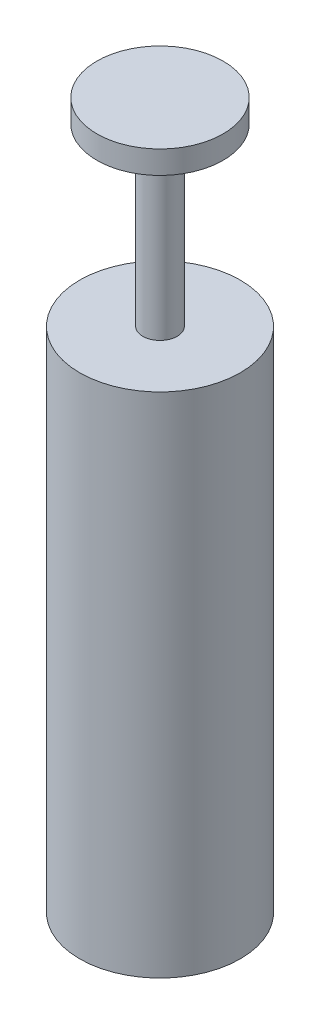
SolidWorks part; units mm, degrees
ref_plane "Front" through (0, 0, 0) normal (0, 0, 1) x (1, 0, 0)
ref_plane "Top" through (0, 0, 0) normal (0, 1, 0) x (1, 0, 0)
ref_plane "Right" through (0, 0, 0) normal (1, 0, 0) x (0, 0, -1)
sketch "Sketch1" plane through (0, 0, 0) normal (1, 0, 0) x (0, 0, -1)
  line L0 (0, 0) -> (0, 195.326) construction
  line L1 (0, 195.326) -> (17.4625, 195.326)
  line L2 (17.4625, 195.326) -> (17.4625, 188.976)
  line L3 (17.4625, 188.976) -> (4.7625, 188.976)
  line L4 (4.7625, 188.976) -> (4.7625, 140.462)
  line L5 (4.7625, 140.462) -> (22.225, 140.462)
  line L6 (22.225, 140.462) -> (22.225, 0)
  line L7 (22.225, 0) -> (0, 0)
  line L8 (0, 0) -> (0, 195.326)
  dimension "D1" = 195.326
  dimension "D2" = 34.925
  dimension "D3" = 44.45
  dimension "D4" = 9.525
  dimension "D5" = 6.35
  dimension "D6" = 48.514
revolve "Revolve1" add sketch "Sketch1" angle 360 about L0
